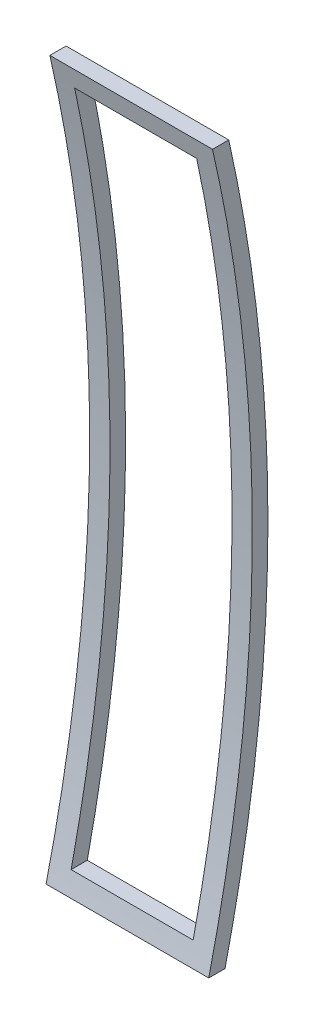
SolidWorks part; units mm, degrees
ref_plane "Front Plane" through (0, 0, 0) normal (0, 0, 1) x (1, 0, 0)
ref_plane "Top Plane" through (0, 0, 0) normal (0, 1, 0) x (1, 0, 0)
ref_plane "Right Plane" through (0, 0, 0) normal (1, 0, 0) x (0, 0, -1)
sketch "Sketch1" plane through (0, 0, 0) normal (0, 0, 1) x (1, 0, 0)
  line L1 (0, 2235.2) -> (508, 2235.2)
  line L2 (0, 2235.2) -> (0, 0)
  line L3 (0, 0) -> (508, 0)
  line L4 (508, 2235.2) -> (508, 0)
extrude "Boss-Extrude1" add sketch "Sketch1" along normal mid plane 635
sketch "Sketch3" plane through (0, 0, 0) normal (1, 0, 0) x (0, 0, -1)
  line L0 (11.8216, 2235.2) -> (-317.5, 2235.2)
  line L1 (-317.5, 2235.2) -> (-317.5, 0)
  line L2 (-317.5, 0) -> (0, 0)
  line L3 (62.4417, 2235.2) -> (317.5, 2235.2)
  line L4 (62.4417, 2235.2) -> (11.8216, 2235.2)
  line L5 (0, 0) -> (50.8, 0)
  line L6 (317.5, 2235.2) -> (317.5, 0)
  line L7 (317.5, 0) -> (50.8, 0)
  spline S4 degree 3 poles (11.8216, 2235.2) (53.5781, 2051.5928) (85.2226, 1866.2074) (107.4342, 1667.2291) (108.6989, 1655.516) (111.1425, 1632.0899) (114.6799, 1596.9456) (122.0367, 1514.9065) (126.802, 1444.5257) (134.2708, 1303.682) (136.5012, 1209.6766) (135.8288, 1092.0317) (135.3675, 1056.7279) (134.5163, 1021.4085) (133.862, 997.8588) (133.4917, 986.0869) (131.4249, 927.2647) (129.083, 880.3042) (120.0173, 739.7108) (111.2537, 646.366) (77.0023, 367.4556) (43.556, 183.014) (0, 0) knots 0 0 0 0 0.25 0.25 0.265625 0.265625 0.28125 0.3125 0.375 0.375 0.5 0.5 0.53125 0.546875 0.546875 0.5625 0.5625 0.625 0.625 0.75 0.75 1 1 1 1
  spline S5 degree 3 poles (50.8, 0) (93.7569, 183.2826) (126.7063, 367.9385) (160.4178, 647.0786) (169.0357, 740.4847) (176.4566, 857.7023) (178.4314, 892.9021) (180.027, 928.1539) (181.0062, 951.6667) (181.4534, 963.427) (183.4763, 1022.2128) (184.4137, 1069.2235) (185.1879, 1210.2019) (182.9868, 1304.116) (175.6276, 1444.8803) (171.716, 1503.5098) (166.7502, 1562.1116) (164.6796, 1585.5501) (163.6019, 1597.27) (160.2444, 1632.4082) (157.8398, 1655.8074) (134.7121, 1866.1648) (103.5882, 2051.4759) (62.4417, 2235.2) knots 0 0 0 0 0.25 0.25 0.375 0.375 0.40625 0.421875 0.421875 0.4375 0.4375 0.5 0.5 0.625 0.625 0.6875 0.703125 0.703125 0.71875 0.71875 0.75 0.75 1 1 1 1
  dimension "D1" = 50.8
extrude "Cut-Extrude1" cut sketch "Sketch3" along normal through all contours S4 L0 L1 L2 | S5 L7 L6 L3
sketch "Sketch4" plane through (0, 0, 0) normal (0, 0, 1) x (1, 0, 0)
  line L14 (63.5, 63.5) -> (444.5, 63.5)
  line L15 (63.5, 2171.7) -> (63.5, 63.5)
  line L16 (444.5, 63.5) -> (444.5, 2171.7)
  line L17 (444.5, 2171.7) -> (63.5, 2171.7)
  line L18 (63.5, 63.5) -> (444.5, 63.5)
  line L19 (63.5, 2171.7) -> (63.5, 63.5)
  line L20 (444.5, 63.5) -> (444.5, 2171.7)
  line L21 (444.5, 2171.7) -> (63.5, 2171.7)
  dimension "D1" = 63.5
extrude "Cut-Extrude2" cut sketch "Sketch4" against normal blind 635
ref_plane "Plane1" through (441.96, 0, 0) normal (-1, 0, 0) x (0, 0, 1)
ref_plane "Plane2" through (66.04, 0, 0) normal (1, 0, 0) x (0, 0, -1)
ref_plane "Plane3" through (0, 2169.16, 0) normal (0, -1, 0) x (-1, 0, 0)
ref_plane "Plane4" through (0, 0, 0) normal (0, 0.0053, 1) x (1, 0, 0)
